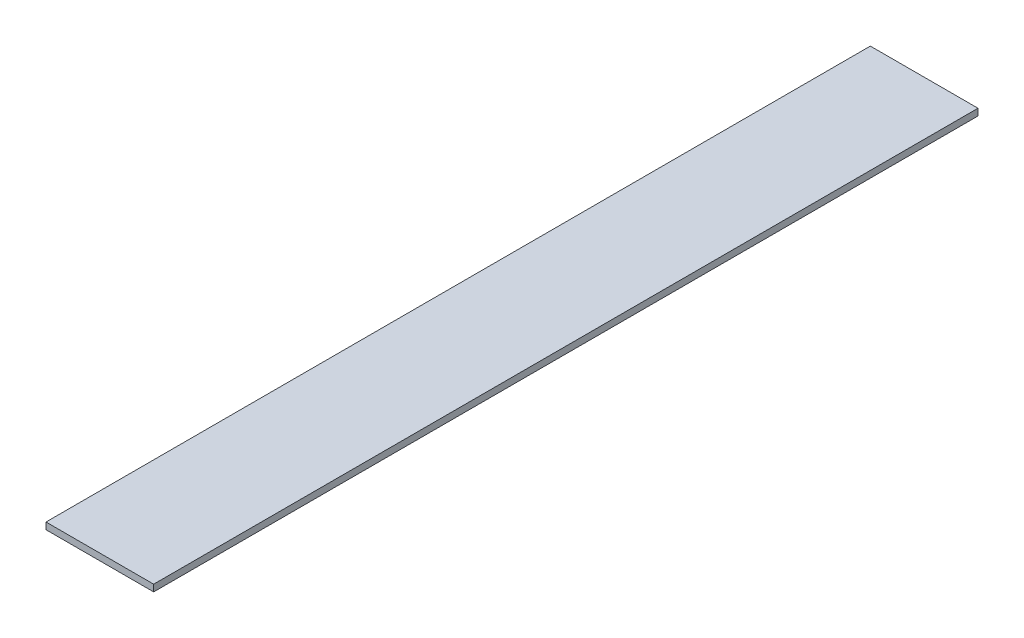
SolidWorks part; units mm, degrees
ref_plane "前视基准面" through (0, 0, 0) normal (0, 0, 1) x (1, 0, 0)
ref_plane "上视基准面" through (0, 0, 0) normal (0, 1, 0) x (1, 0, 0)
ref_plane "右视基准面" through (0, 0, 0) normal (1, 0, 0) x (0, 0, -1)
sketch "草图1" plane through (0, 0, 0) normal (0, 1, 0) x (1, 0, 0)
  line L1 (0, 0) -> (32, 0)
  line L2 (0, 0) -> (0, 245)
  line L3 (0, 245) -> (32, 245)
  line L4 (32, 0) -> (32, 245)
  dimension "D1" = 32
  dimension "D2" = 245
extrude "凸台-拉伸1" add sketch "草图1" along normal blind 2
